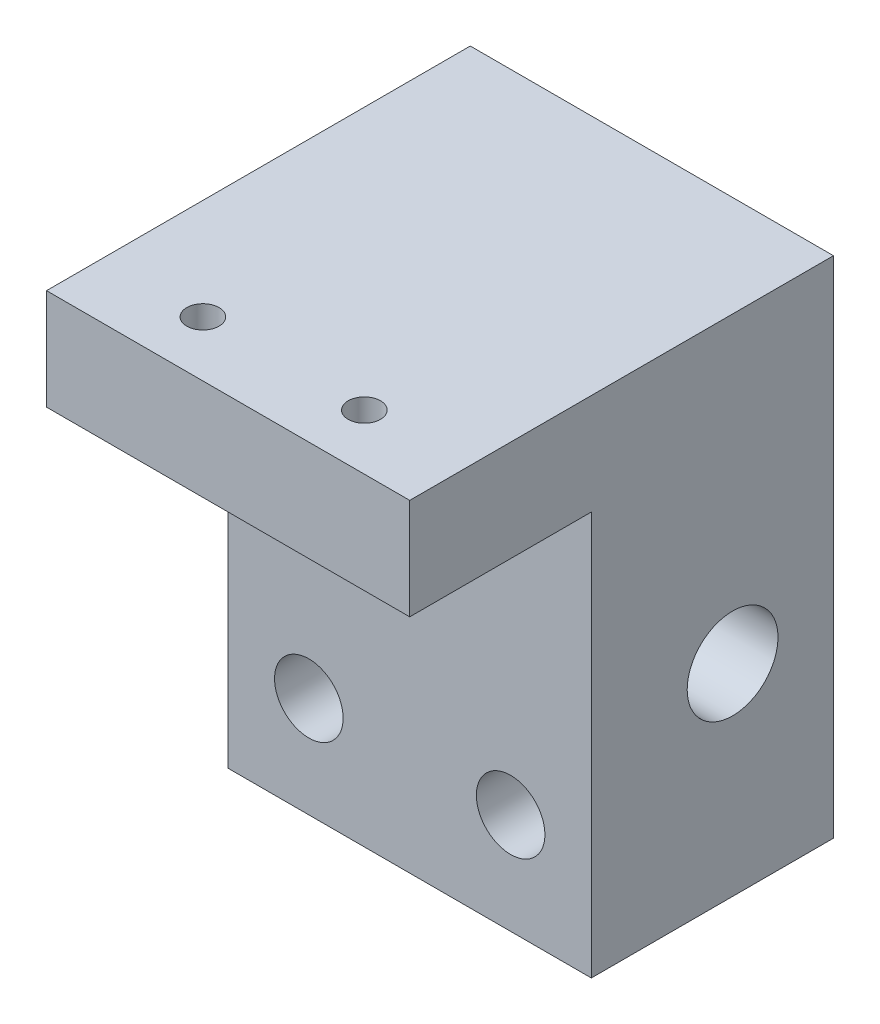
SolidWorks part; units mm, degrees
ref_plane "前视基准面" through (0, 0, 0) normal (0, 0, 1) x (1, 0, 0)
ref_plane "上视基准面" through (0, 0, 0) normal (0, 1, 0) x (1, 0, 0)
ref_plane "右视基准面" through (0, 0, 0) normal (1, 0, 0) x (0, 0, -1)
other "Configuration Table"
sketch "草图1" plane through (0, 0, 0) normal (0, 1, 0) x (1, 0, 0)
  line L1 (0, 0) -> (36, 0)
  line L2 (0, 0) -> (0, 24)
  line L3 (0, 24) -> (36, 24)
  line L4 (36, 0) -> (36, 24)
  dimension "D1" = 36
  dimension "D2" = 24
extrude "凸台-拉伸1" add sketch "草图1" along normal blind 50
sketch "草图2" plane through (0, 0, 0) normal (-1, 0, 0) x (0, 0, 1)
  line L0 (-24, 0) -> (0, 0) construction
  line L1 (-24, 50) -> (-24, 0) construction
  circle A0 centre (-14, 20) radius 4.5
  dimension "D1" = 20
  dimension "D2" = 9
  dimension "D3" = 10
extrude "切除-拉伸1" cut sketch "草图2" against normal up to surface (36 mm away) up to face at (36, 25, -12)
sketch "草图3" plane through (0, 0, 0) normal (0, 0, 1) x (1, 0, 0)
  line L0 (0, 0) -> (36, 0) construction
  line L1 (0, 50) -> (0, 0) construction
  circle A0 centre (8, 10) radius 3.4
  circle A1 centre (28, 10) radius 3.4
  dimension "D1" = 6.8
  dimension "D2" = 6.8
  dimension "D3" = 10
  dimension "D4" = 20
  dimension "D5" = 8
extrude "切除-拉伸2" cut sketch "草图3" against normal blind 6
sketch "草图5" plane through (36, 0, 0) normal (1, 0, 0) x (0, 0, -1)
  line L1 (0, 50) -> (0, 0) construction
  line L2 (0, 50) -> (-18, 50)
  line L3 (0, 50) -> (0, 40)
  line L4 (0, 40) -> (-18, 40)
  line L5 (-18, 50) -> (-18, 40)
  line L6 (-18, 50) -> (27, 50) construction
  dimension "D1" = 18
  dimension "D2" = 10
extrude "凸台-拉伸2" add sketch "草图5" against normal up to surface (36 mm away) up to face at (0, 20, -9.5)
sketch "草图6" plane through (0, 50, 0) normal (0, 1, 0) x (1, 0, 0)
  line L0 (0, 24) -> (0, -18) construction
  line L1 (36, 24) -> (0, 24) construction
  circle A0 centre (26, -12.5) radius 1.6
  circle A1 centre (10, -12.5) radius 1.6
  point P6 (0, 0)
  point P8 (9.3829, -6.1883)
  dimension "D1" = 3.2
  dimension "D2" = 3.2
  dimension "D3" = 16
  dimension "D4" = 10
  dimension "D5" = 36.5
extrude "切除-拉伸3" cut sketch "草图6" against normal blind 5
